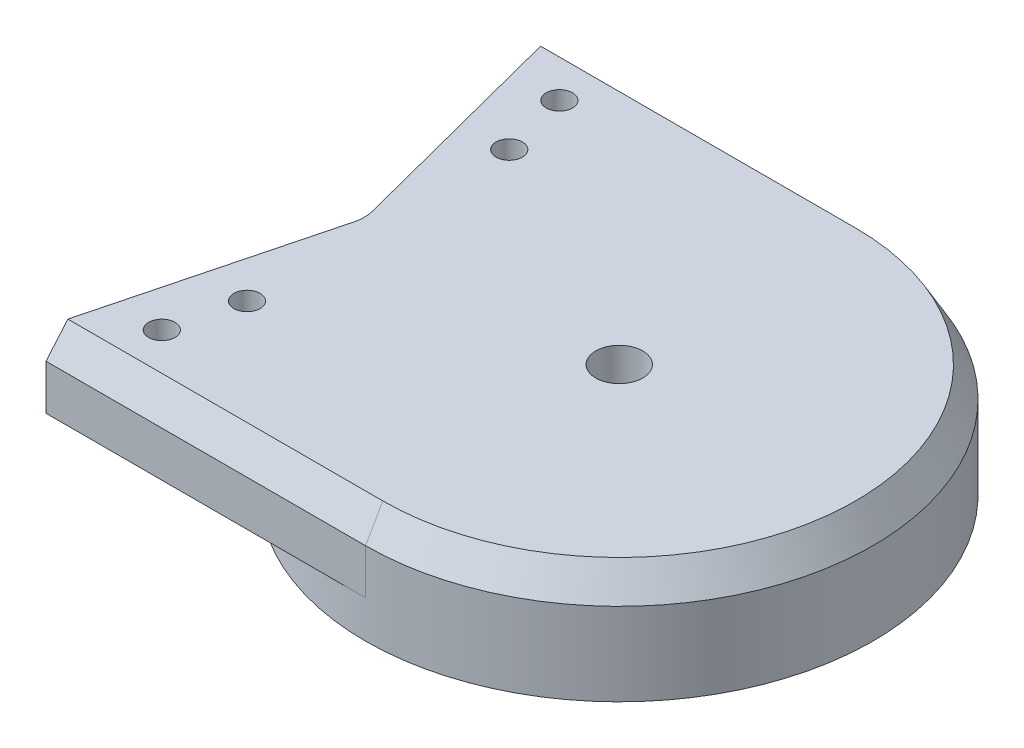
SolidWorks part; units mm, degrees
ref_plane "Alzado" through (0, 0, 0) normal (0, 0, 1) x (1, 0, 0)
ref_plane "Planta" through (0, 0, 0) normal (0, 1, 0) x (1, 0, 0)
ref_plane "Vista lateral" through (0, 0, 0) normal (1, 0, 0) x (0, 0, -1)
sketch "Croquis2" plane through (0, 0, 0) normal (0, 1, 0) x (1, 0, 0)
  line L0 (32.725, -35) -> (-35, -35) construction
  line L1 (52.1828, -19.7053) -> (38, 35) construction
  line L2 (-35, 35) -> (38, 35) construction
  line L3 (-35, -35) -> (-35, 35) construction
  line L4 (32.725, -35) -> (-35, -35)
  line L5 (52.1828, -19.7053) -> (38, 35)
  line L6 (-35, 35) -> (38, 35)
  line L7 (-35, -35) -> (-35, 35)
  arc A0 (32.5, -32.5) -> (54.1538, -20.7774) centre (46.5, -32.5) ccw construction
  arc A1 (52.1828, -19.7053) -> (32.5, -32.5) centre (46.5, -32.5) ccw construction
  arc A2 (32.5, -32.5) -> (32.725, -35) centre (46.5, -32.5) ccw
  arc A3 (52.1828, -19.7053) -> (32.5, -32.5) centre (46.5, -32.5) ccw
  circle A4 centre (1.5, -1.5) radius 24 construction
  circle A5 centre (1.5, -1.5) radius 24 construction
extrude "Saliente-Extruir2" add sketch "Croquis2" along normal blind 23
sketch "Croquis7" plane through (0, 23, 0) normal (0, 1, 0) x (1, 0, 0)
  circle A0 centre (1.5, -1.5) radius 24 construction
  circle A1 centre (1.5, -1.5) radius 24 construction
  circle A2 centre (1.5, -1.5) radius 20
  dimension "D1" = 40
extrude "Cortar-Extruir1" cut sketch "Croquis7" against normal blind 16 contours A2
sketch "Croquis8" plane through (0, 7, 0) normal (0, 1, 0) x (1, 0, 0)
  circle A0 centre (1.5, -1.5) radius 10.25
  circle A1 centre (1.5, -1.5) radius 20 construction
  dimension "D1" = 20.5
extrude "Cortar-Extruir2" cut sketch "Croquis8" against normal through all
sketch "Croquis9" plane through (0, 23, 0) normal (0, 1, 0) x (1, 0, 0)
  line L0 (-35, 35) -> (-35, -35) construction
  line L1 (38, 35) -> (-35, 35) construction
  line L2 (-35, 35) -> (-35, -100)
  line L4 (38, 35) -> (-35, 35)
  line L6 (46.5, -32.5) -> (-35, -32.5) construction
  line L7 (38, 35) -> (54.8494, -29.9904)
  line L9 (52.1828, -19.7053) -> (38, 35) construction
  line L10 (38, -100) -> (54.8494, -35.0096)
  line L11 (38, -100) -> (-35, -100)
  arc A0 (52.1828, -19.7053) -> (32.725, -35) centre (46.5, -32.5) ccw construction
  circle A2 centre (1.5, -1.5) radius 20 construction
  circle A3 centre (1.5, -1.5) radius 20
  arc A4 (52.1828, -19.7053) -> (32.725, -35) centre (46.5, -32.5) ccw construction
  circle A5 centre (46.5, -32.5) radius 3.075
  arc A6 (54.8494, -35.0096) -> (54.8494, -29.9904) centre (45.1694, -32.5) ccw
  circle A7 centre (1.5, -1.5) radius 10.25 construction
  circle A8 centre (1.5, -1.5) radius 10.25 construction
  circle A9 centre (1.5, -63.5) radius 10.25
  point P19 (55.5, -32.5)
  dimension "D1" = 10
  dimension "D2" = 6.15
extrude "Saliente-Extruir3" add sketch "Croquis9" along normal blind 32
sketch "Croquis10" plane through (0, 23, 0) normal (0, -1, 0) x (1, 0, 0)
  line L0 (46.5, 32.5) -> (-35, 32.5) construction
  line L1 (-35, -35) -> (-35, 35) construction
  circle A0 centre (1.5, 1.5) radius 20 construction
  circle A1 centre (1.5, 1.5) radius 20 construction
  circle A2 centre (1.5, 63.5) radius 20
extrude "Cortar-Extruir3" cut sketch "Croquis10" against normal through all from offset 7 offset against normal yes
sketch "Croquis11" plane through (0, 55, 0) normal (0, 1, 0) x (1, 0, 0)
  line L0 (46.5, -32.5) -> (123, -32.5) construction
  line L1 (38, 35) -> (-35, 35) construction
  line L2 (123, 35) -> (-35, 35)
  line L3 (-35, 35) -> (-35, -100)
  line L4 (-35, -100) -> (123, -100)
  arc A0 (123, -100) -> (123, 35) centre (123, -32.5) ccw
  circle A1 centre (46.5, -32.5) radius 3.075 construction
  circle A2 centre (1.5, -63.5) radius 20 construction
  circle A3 centre (1.5, -1.5) radius 20 construction
  circle A4 centre (46.5, -32.5) radius 3.075
  circle A5 centre (1.5, -63.5) radius 20
  circle A6 centre (1.5, -1.5) radius 20
  dimension "D1" = 76.5
extrude "Saliente-Extruir4" add sketch "Croquis11" along normal blind 20
sketch "Croquis12" plane through (0, 55, 0) normal (0, -1, 0) x (1, 0, 0)
  circle A0 centre (123, 32.5) radius 63
  dimension "D1" = 126
extrude "Cortar-Extruir4" cut sketch "Croquis12" against normal blind 3
sketch "Croquis13" plane through (0, 58, 0) normal (0, -1, 0) x (1, 0, 0)
  circle A0 centre (123, 32.5) radius 55
  circle A1 centre (123, 32.5) radius 63 construction
  dimension "D1" = 110
extrude "Cortar-Extruir5" cut sketch "Croquis13" against normal blind 10
sketch "Croquis14" plane through (0, 75, 0) normal (0, 1, 0) x (1, 0, 0)
  line L0 (-35, -100) -> (123, -100) construction
  line L1 (123, 35) -> (-35, 35) construction
  line L2 (-35, 35) -> (-35, -100) construction
  line L3 (-35, -100) -> (123, -100)
  line L4 (123, 35) -> (-35, 35)
  line L5 (-35, 35) -> (-35, -100)
  arc A0 (123, -100) -> (123, 35) centre (123, -32.5) ccw construction
  arc A1 (123, -100) -> (123, 35) centre (123, -32.5) ccw
extrude "Saliente-Extruir5" add sketch "Croquis14" along normal blind 10
chamfer "Chaflán1" distance 8 angle 30 3 edges at (44, 85, -35) (190.5, 85, 32.5) (44, 85, 100)
sketch "Croquis15" plane through (0, 68, 0) normal (0, -1, 0) x (1, 0, 0)
  circle A0 centre (123, 32.5) radius 6.25
  dimension "D1" = 12.5
extrude "Cortar-Extruir6" cut sketch "Croquis15" against normal through all
sketch "Croquis17" plane through (0, 0, 0) normal (0, -1, 0) x (1, 0, 0)
  line L0 (1.5, 1.5) -> (16.5, 1.5) construction
  line L1 (1.5, 1.5) -> (13.6244, 8.5) construction
  circle A0 centre (1.5, 1.5) radius 15 construction
  circle A1 centre (1.5, 1.5) radius 14 construction
  circle A2 centre (16.5, 1.5) radius 1.5
  circle A3 centre (-6, -11.4904) radius 1.5
  circle A4 centre (-6, 14.4904) radius 1.5
  circle A6 centre (13.6244, 8.5) radius 1.5
  circle A7 centre (1.5, -12.5) radius 1.5
  circle A8 centre (1.5, 1.5) radius 14 construction
  circle A9 centre (-10.6244, 8.5) radius 1.5
  circle A10 centre (1.5, 1.5) radius 14 construction
  point P13 (1.5, 1.5)
  point P22 (1.5, 1.5)
  dimension "D1" = 30
  dimension "D2" = 28
  dimension "D3" = 3
  dimension "D5" = 30
  dimension "D4" = 3
  dimension "D6" = 3
extrude "Cortar-Extruir7" cut sketch "Croquis17" against normal up to next
sketch "Croquis19" plane through (0, 23, 0) normal (0, -1, 0) x (1, 0, 0)
  line L0 (1.5, 63.5) -> (16.5, 63.5) construction
  line L1 (1.5, 63.5) -> (13.6244, 70.5) construction
  circle A0 centre (1.5, 63.5) radius 15 construction
  circle A1 centre (1.5, 63.5) radius 14 construction
  circle A2 centre (16.5, 63.5) radius 1.5
  circle A3 centre (-6, 50.5096) radius 1.5
  circle A4 centre (-6, 76.4904) radius 1.5
  circle A6 centre (13.6244, 70.5) radius 1.5
  circle A7 centre (1.5, 49.5) radius 1.5
  circle A8 centre (-10.6244, 70.5) radius 1.5
  point P13 (1.5, 63.5)
  point P20 (1.5, 63.5)
  dimension "D1" = 30
  dimension "D2" = 28
  dimension "D3" = 3
  dimension "D6" = 30
  dimension "D4" = 3
  dimension "D5" = 3
extrude "Cortar-Extruir9" cut sketch "Croquis19" against normal up to next
sketch "Croquis20" plane through (0, 0, 0) normal (0, -1, 0) x (1, 0, 0)
  line L1 (16.5, 1.5) -> (41.2646, 1.5) construction
  line L2 (46.3749, 21.211) -> (32.192, -33.4942)
  line L3 (42.3657, 5.7471) -> (39.7731, -4.2529)
  line L4 (39.4617, 9.5) -> (19.8303, 9.5)
  line L5 (36.8691, -6.5) -> (19.8303, -6.5)
  circle A0 centre (1.5, 1.5) radius 20 construction
  arc A1 (19.8303, -6.5) -> (19.8303, 9.5) centre (1.5, 1.5) ccw
  arc A2 (39.7731, -4.2529) -> (36.8691, -6.5) centre (36.8691, -3.5) cw
  arc A3 (42.3657, 5.7471) -> (39.4617, 9.5) centre (39.4617, 6.5) ccw
  dimension "D3" = 3
  dimension "D2" = 16
  dimension "D1" = 6
extrude "Cortar-Extruir10" cut sketch "Croquis20" against normal blind 50
sketch "Croquis21" plane through (0, 23, 0) normal (0, -1, 0) x (1, 0, 0)
  line L0 (19.8303, -6.5) -> (36.8691, -6.5) construction
  line L1 (39.7731, -4.2529) -> (42.3657, 5.7471) construction
  line L2 (39.4617, 9.5) -> (19.8303, 9.5) construction
  line L3 (19.8303, -6.5) -> (36.8691, -6.5) construction
  line L4 (39.7731, -4.2529) -> (42.3657, 5.7471) construction
  line L5 (39.4617, 9.5) -> (19.8303, 9.5) construction
  line L6 (46.5, 32.5) -> (-35, 32.5) construction
  line L7 (-35, -35) -> (-35, 35) construction
  line L8 (39.4617, 55.5) -> (19.8303, 55.5)
  line L9 (39.7731, 69.2529) -> (42.3657, 59.2529)
  line L10 (19.8303, 71.5) -> (36.8691, 71.5)
  arc A0 (36.8691, -6.5) -> (39.7731, -4.2529) centre (36.8691, -3.5) ccw construction
  arc A1 (42.3657, 5.7471) -> (39.4617, 9.5) centre (39.4617, 6.5) ccw construction
  arc A2 (19.8303, -6.5) -> (19.8303, 9.5) centre (1.5, 1.5) ccw construction
  arc A3 (36.8691, -6.5) -> (39.7731, -4.2529) centre (36.8691, -3.5) ccw construction
  arc A4 (42.3657, 5.7471) -> (39.4617, 9.5) centre (39.4617, 6.5) ccw construction
  arc A5 (19.8303, -6.5) -> (19.8303, 9.5) centre (1.5, 1.5) ccw construction
  arc A6 (19.8303, 71.5) -> (19.8303, 55.5) centre (1.5, 63.5) cw
  arc A7 (42.3657, 59.2529) -> (39.4617, 55.5) centre (39.4617, 58.5) cw
  arc A8 (36.8691, 71.5) -> (39.7731, 69.2529) centre (36.8691, 68.5) cw
extrude "Cortar-Extruir11" cut sketch "Croquis21" against normal blind 50
sketch "Croquis22" plane through (0, 0, 0) normal (0, -1, 0) x (1, 0, 0)
  circle A0 centre (-6, 14.4904) radius 3
  circle A1 centre (-10.6244, 8.5) radius 3
  circle A2 centre (-6, -11.4904) radius 3
  circle A3 centre (1.5, -12.5) radius 3
  circle A4 centre (16.5, 1.5) radius 3
  circle A5 centre (13.6244, 8.5) radius 3
  dimension "D1" = 6
extrude "Cortar-Extruir12" cut sketch "Croquis22" against normal blind 3
sketch "Croquis23" plane through (0, 23, 0) normal (0, -1, 0) x (1, 0, 0)
  circle A0 centre (-6, 76.4904) radius 3
  circle A1 centre (-10.6244, 70.5) radius 3
  circle A2 centre (-6, 50.5096) radius 3
  circle A3 centre (1.5, 49.5) radius 3
  circle A4 centre (16.5, 63.5) radius 3
  circle A5 centre (13.6244, 70.5) radius 3
  dimension "D1" = 6
extrude "Cortar-Extruir13" cut sketch "Croquis23" against normal blind 3
sketch "Croquis25" plane through (0, 23, 0) normal (0, -1, 0) x (1, 0, 0)
  line L0 (1.5, 63.5) -> (-35, 63.5) construction
  line L1 (-35, 35) -> (-35, 100) construction
  line L2 (-35, 35) -> (32.725, 35) construction
  circle A0 centre (-28.75, 63.5) radius 2.5
  circle A1 centre (29, 47) radius 2.5
  dimension "D1" = 5
  dimension "D2" = 6.25
  dimension "D3" = 64
  dimension "D4" = 12
extrude "Cortar-Extruir15" cut sketch "Croquis25" against normal blind 30
sketch "Croquis24" plane through (0, 0, 0) normal (0, -1, 0) x (1, 0, 0)
  line L0 (1.5, 1.5) -> (-35, 1.5) construction
  line L1 (-35, -35) -> (-35, 35) construction
  line L4 (-22, -22) -> (25, -22) construction
  line L5 (-22, -22) -> (-22, 25) construction
  line L6 (-22, 25) -> (25, 25) construction
  line L7 (25, -22) -> (25, 25) construction
  line L8 (-22, -22) -> (25, 25) construction
  line L9 (-22, 25) -> (25, -22) construction
  circle A0 centre (-28.75, 1.5) radius 2.5
  circle A1 centre (25, 25) radius 2.5
  dimension "D1" = 5
  dimension "D2" = 6.25
  dimension "D3" = 47
extrude "Cortar-Extruir14" cut sketch "Croquis24" against normal blind 30
sketch "Croquis26" plane through (0, 55, 0) normal (0, -1, 0) x (1, 0, 0)
  line L2 (49.616, 103.0115) -> (66.4653, 38.0212)
  line L3 (49.616, 103.0115) -> (66.4653, 38.0212) construction
  line L4 (-35, 95.3812) -> (123, 95.3812) construction
  line L5 (46.5, 32.5) -> (123, 32.5) construction
  circle A0 centre (54.1868, 85.3812) radius 2
  circle A1 centre (58.8535, 67.3812) radius 2
  circle A2 centre (58.8535, -2.3812) radius 2
  circle A3 centre (54.1868, -20.3812) radius 2
  dimension "D2" = 10
  dimension "D3" = 18
  dimension "D4" = 4
  dimension "D1" = 12
extrude "Cortar-Extruir16" cut sketch "Croquis26" against normal through all
sketch "Croquis27" plane through (0, 85, 0) normal (0, 1, 0) x (1, 0, 0)
  circle A0 centre (54.1868, 20.3812) radius 3.5
  circle A1 centre (58.8535, 2.3812) radius 3.5
  circle A2 centre (58.8535, -67.3812) radius 3.5
  circle A3 centre (54.1868, -85.3812) radius 3.5
  dimension "D1" = 7
extrude "Cortar-Extruir17" cut sketch "Croquis27" against normal blind 5
sketch "Croquis28" plane through (0, 55, 0) normal (0, -1, 0) x (1, 0, 0)
  line L0 (38, 100) -> (54.8494, 35.0096) construction
  line L1 (55.2228, 81.3853) -> (58.1654, 84.2804)
  line L2 (58.1654, 84.2804) -> (57.1294, 88.2764)
  line L3 (57.1294, 88.2764) -> (53.1508, 89.3771)
  line L4 (53.1508, 89.3771) -> (50.2082, 86.482)
  line L5 (50.2082, 86.482) -> (51.2442, 82.486)
  line L6 (51.2442, 82.486) -> (55.2228, 81.3853)
  line L7 (59.8894, 63.3853) -> (62.832, 66.2804)
  line L8 (62.832, 66.2804) -> (61.7961, 70.2764)
  line L9 (61.7961, 70.2764) -> (57.8175, 71.3771)
  line L10 (57.8175, 71.3771) -> (54.8749, 68.482)
  line L11 (54.8749, 68.482) -> (55.9109, 64.486)
  line L12 (55.9109, 64.486) -> (59.8894, 63.3853)
  line L13 (59.8894, 1.6147) -> (55.9109, 0.514)
  line L14 (55.9109, 0.514) -> (54.8749, -3.482)
  line L15 (54.8749, -3.482) -> (57.8175, -6.3771)
  line L16 (57.8175, -6.3771) -> (61.7961, -5.2764)
  line L17 (61.7961, -5.2764) -> (62.832, -1.2804)
  line L18 (62.832, -1.2804) -> (59.8894, 1.6147)
  line L19 (55.2228, -16.3853) -> (51.2442, -17.486)
  line L20 (51.2442, -17.486) -> (50.2082, -21.482)
  line L21 (50.2082, -21.482) -> (53.1508, -24.3771)
  line L22 (53.1508, -24.3771) -> (57.1294, -23.2764)
  line L23 (57.1294, -23.2764) -> (58.1654, -19.2804)
  line L24 (58.1654, -19.2804) -> (55.2228, -16.3853)
  line L25 (52.1828, 19.7053) -> (38, -35) construction
  circle A0 centre (54.1868, 85.3812) radius 3.575 construction
  circle A1 centre (58.8535, 67.3812) radius 3.575 construction
  circle A2 centre (58.8535, -2.3812) radius 3.575 construction
  circle A3 centre (54.1868, -20.3812) radius 3.575 construction
  dimension "D1" = 7.15
extrude "Cortar-Extruir18" cut sketch "Croquis28" against normal blind 3.25
sketch "Croquis29" plane through (0, 68, 0) normal (0, -1, 0) x (1, 0, 0)
  circle A0 centre (123, 32.5) radius 37.5 construction
  circle A1 centre (160.5, 32.5) radius 1.5
  circle A2 centre (141.75, 0.024) radius 1.5
  circle A3 centre (104.25, 0.024) radius 1.5
  circle A4 centre (85.5, 32.5) radius 1.5
  circle A5 centre (104.25, 64.976) radius 1.5
  circle A6 centre (141.75, 64.976) radius 1.5
  point P18 (123, 32.5)
  dimension "D1" = 75
  dimension "D2" = 3
  dimension "D3" = 6
extrude "Cortar-Extruir19" [suppressed] cut sketch "Croquis29" against normal blind 10
sketch "Croquis30" plane through (0, 55, 0) normal (0, -1, 0) x (1, 0, 0)
  line L0 (123, 100) -> (-35, 100)
  line L1 (-35, 100) -> (-35, -35)
  line L2 (-35, -35) -> (123, -35)
  arc A0 (123, 100) -> (123, -35) centre (123, 32.5) ccw
  arc A1 (123, -35) -> (123, 100) centre (123, 32.5) ccw construction
extrude "Cortar-Extruir20" cut sketch "Croquis30" against normal blind 10 and the other way through all
sketch "Croquis31" plane through (0, 65, 0) normal (0, -1, 0) x (1, 0, 0)
  line L0 (46.5, 32.5) -> (-35, 32.5) construction
  line L1 (-22, 40) -> (25, 40) construction
  line L2 (-22, 40) -> (-22, 87) construction
  line L3 (-22, 87) -> (25, 87) construction
  line L4 (25, 40) -> (25, 87) construction
  line L5 (-22, 40) -> (25, 87) construction
  line L6 (-22, 87) -> (25, 40) construction
  line L7 (-35, 100) -> (-35, -35) construction
  circle A0 centre (-22, 87) radius 2.5
  circle A1 centre (25, 87) radius 2.5
  circle A2 centre (25, -22) radius 2.5
  circle A3 centre (-22, -22) radius 2.5
  point P0 (1.5, 63.5)
  dimension "D2" = 5
  dimension "D1" = 47
extrude "Cortar-Extruir21" cut sketch "Croquis31" against normal through all
sketch "Croquis32" plane through (0, 85, 0) normal (0, 1, 0) x (1, 0, 0)
  circle A0 centre (-22, 22) radius 4.5
  circle A1 centre (25, 22) radius 4.5
  circle A2 centre (-22, -87) radius 4.5
  circle A3 centre (25, -87) radius 4.5
  dimension "D1" = 9
extrude "Cortar-Extruir22" cut sketch "Croquis32" against normal blind 5
sketch "Croquis33" plane through (0, 68, 0) normal (0, -1, 0) x (1, 0, 0)
  circle A0 centre (123, 32.5) radius 55 construction
  circle A1 centre (123, 32.5) radius 55
  circle A2 centre (123, 32.5) radius 6.25 construction
  circle A3 centre (123, 32.5) radius 6.25
extrude "Saliente-Extruir6" add sketch "Croquis33" along normal blind 4
sketch "Croquis34" plane through (0, 64, 0) normal (0, -1, 0) x (1, 0, 0)
  circle A0 centre (123, 32.5) radius 16.85
  circle A1 centre (123, 32.5) radius 6.25 construction
  circle A2 centre (123, 32.5) radius 6.25
  dimension "D1" = 33.7
extrude "Saliente-Extruir7" add sketch "Croquis34" along normal blind 3.35
sketch "Croquis35" plane through (0, 60.65, 0) normal (0, -1, 0) x (1, 0, 0)
  circle A0 centre (123, 32.5) radius 10
  circle A1 centre (123, 32.5) radius 6.25 construction
  circle A2 centre (123, 32.5) radius 6.25
  dimension "D1" = 20
extrude "Saliente-Extruir8" add sketch "Croquis35" along normal blind 29
sketch "Croquis36" plane through (0, 65, 0) normal (0, -1, 0) x (1, 0, 0)
  line L0 (58.8535, -2.3812) -> (54.1868, -20.3812) construction
  line L1 (58.8535, 67.3812) -> (54.1868, 85.3812) construction
  line L2 (38, -35) -> (54.8494, 29.9904)
  line L3 (-35, -35) -> (123, -35) construction
  line L4 (54.8494, 35.0096) -> (38, 100)
  line L5 (123, 100) -> (-35, 100) construction
  line L6 (38, 100) -> (-35, 100)
  line L7 (-35, 100) -> (-35, -35)
  line L8 (-35, -35) -> (38, -35)
  arc A1 (54.8494, 35.0096) -> (54.8494, 29.9904) centre (45.1694, 32.5) cw
  point P17 (46.5, 32.5)
  point P19 (55.5, 32.5)
  dimension "D2" = 10
  dimension "D1" = 12
extrude "Cortar-Extruir23" cut sketch "Croquis36" against normal through all
sketch "Croquis37" plane through (0, 64, 0) normal (0, -1, 0) x (1, 0, 0)
  circle A0 centre (123, 32.5) radius 25
  circle A1 centre (123, 32.5) radius 42.5
  dimension "D1" = 85
  dimension "D2" = 50
extrude "Cortar-Extruir24" cut sketch "Croquis37" against normal blind 8
